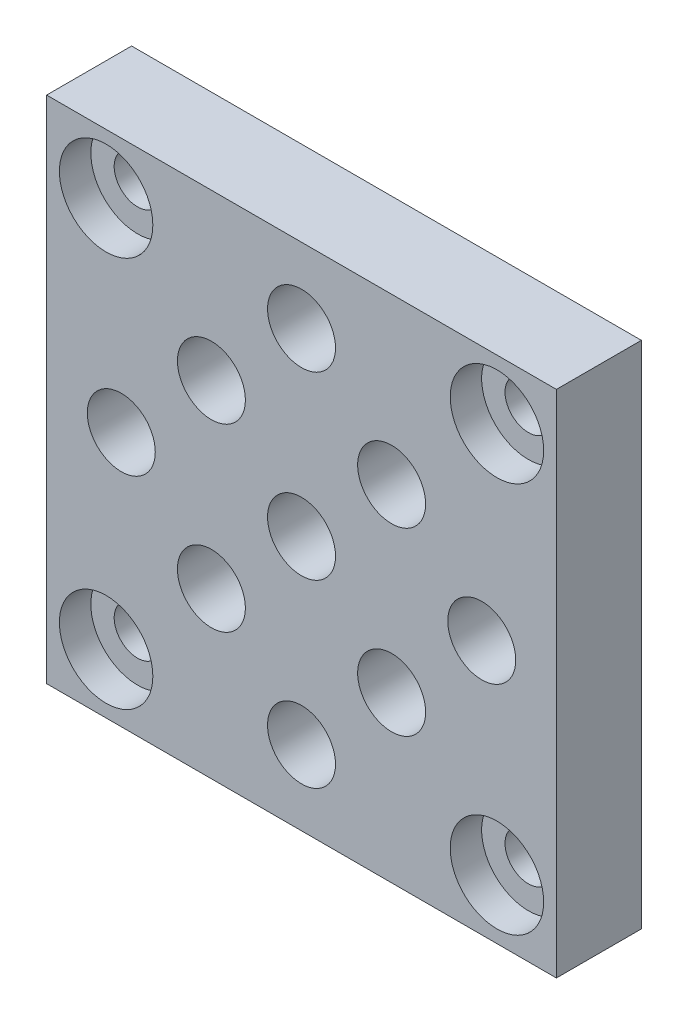
SolidWorks part; units mm, degrees
ref_plane "Front Plane" through (0, 0, 0) normal (1, 0, 0) x (0, 1, 0)
ref_plane "Top Plane" through (0, 0, 0) normal (0, 0, 1) x (0, 1, 0)
ref_plane "Right Plane" through (0, 0, 0) normal (0, 1, 0) x (-1, 0, 0)
sketch "Sketch1" plane through (0, 0, 0) normal (0, 0, 1) x (0, 1, 0)
  line L1 (-30, -30) -> (30, -30)
  line L2 (-30, -30) -> (-30, 30)
  line L3 (-30, 30) -> (30, 30)
  line L4 (30, -30) -> (30, 30)
  line L5 (-30, -30) -> (30, 30) construction
  line L6 (-30, 30) -> (30, -30) construction
  point P0 (0, 0)
  dimension "D1" = 60
extrude "Boss-Extrude1" add sketch "Sketch1" along normal mid plane 10
sketch "Sketch2" plane through (0, 0, 5) normal (0, 0, 1) x (1, 0, 0)
  line L1 (-23, -23) -> (23, -23)
  line L2 (-23, -23) -> (-23, 23)
  line L3 (-23, 23) -> (23, 23)
  line L4 (23, -23) -> (23, 23)
  line L5 (-23, -23) -> (23, 23) construction
  line L6 (-23, 23) -> (23, -23) construction
  circle A0 centre (0, -21.2132) radius 4
  point P0 (0, 0)
  dimension "D4" = 8
  dimension "D1" = 46
  dimension "D2" = 15
  dimension "D3" = 15
extrude "Cut-Extrude1" cut sketch "Sketch2" against normal through all contours A0
pattern_linear "LPattern1" count 3 spacing 15 along (0.7071, 0.7071, 0) count 3 spacing 15 along (-0.7071, 0.7071, 0) of "Cut-Extrude1"
hole_wizard "CBORE for M5 Pan Head Screw1" positions "3DSketch1" profile "Sketch3" counterbore size "M5" standard "ISO" end condition through all
sketch3d "3DSketch1"
  point P0 (-23, 23, 5)
  point P3 (23, 23, 5)
  point P6 (23, -23, 5)
  point P9 (-23, -23, 5)
sketch "Sketch3" plane through (-23, 23, 5) normal (1, 0, 0) x (0, -1, 0)
  line L0 (0, 0) -> (0, 10)
  line L1 (0, 10) -> (2.75, 10)
  line L3 (2.75, 10) -> (2.75, 3.7)
  line L4 (2.75, 3.7) -> (5.5, 3.7)
  line L5 (5.5, 3.7) -> (5.5, 0)
  line L7 (5.5, 0) -> (0, 0)
  line L11 (0, -6.35) -> (0, 107.95) construction
  dimension "Thru Hole Dia." = 5.5
  dimension "Thru Hole Depth" = 10
  dimension "C'Bore Dia." = 11
  dimension "C'Bore Depth" = 3.7
hole_wizard "M5 Tapped Hole1" [suppressed] positions "3DSketch2" profile "Sketch5" tap size "M5" standard "ISO"
sketch3d "3DSketch2"
  point P0 (-23, -23, 5)
  point P3 (-23, 23, 5)
  point P6 (23, 23, 5)
  point P9 (23, -23, 5)
sketch "Sketch5" plane through (-23, -23, 5) normal (1, 0, 0) x (0, -1, 0)
  line L0 (0, 0) -> (0, 10)
  line L1 (0, 10) -> (2.1, 10)
  line L2 (2.1, 10) -> (2.1, 0)
  line L5 (2.1, 0) -> (0, 0)
  line L11 (0, -6.35) -> (0, 107.95) construction
  dimension "Thru Tap Drill Dia." = 4.2
  dimension "Thru Tap Drill Depth" = 10
cosmetic thread "Hole Thread1" [suppressed] parameters "D2"=5
cosmetic thread "Hole Thread2" [suppressed] parameters "D2"=5
cosmetic thread "Hole Thread3" [suppressed] parameters "D2"=5
cosmetic thread "Hole Thread4" [suppressed] parameters "D2"=5
